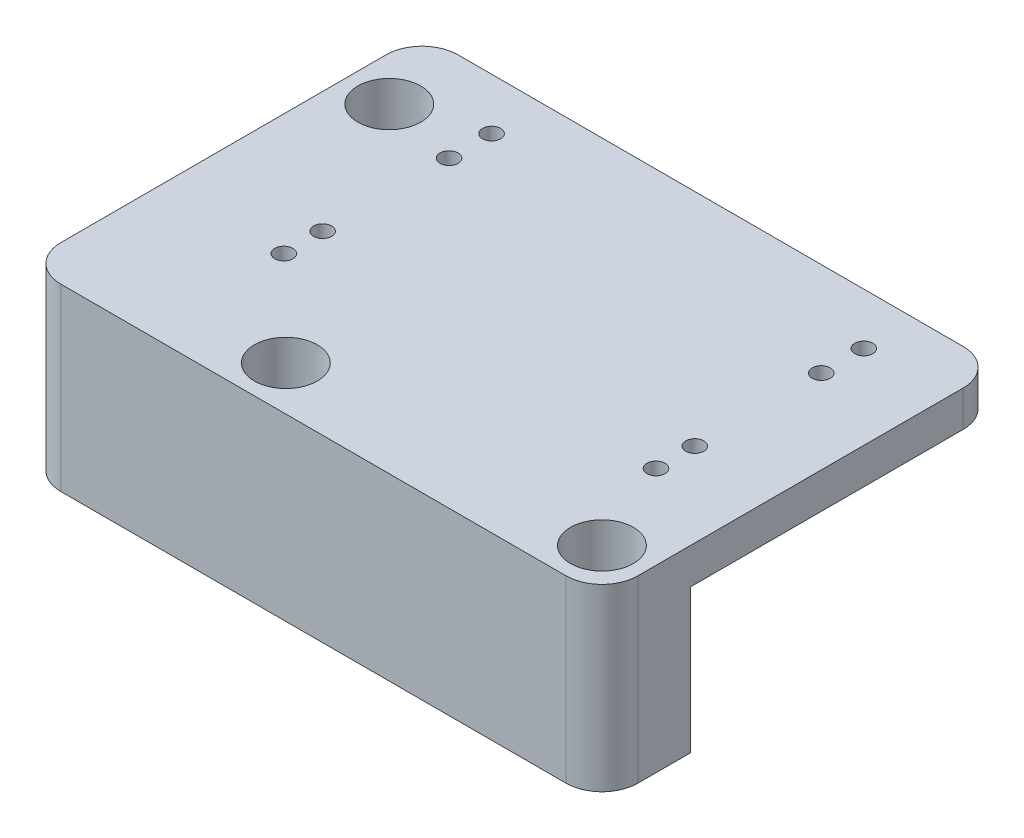
SolidWorks part; units mm, degrees
material "ABS"
ref_plane "Front Plane" through (0, 0, 0) normal (0, 0, 1) x (1, 0, 0)
ref_plane "Top Plane" through (0, 0, 0) normal (0, 1, 0) x (1, 0, 0)
ref_plane "Right Plane" through (0, 0, 0) normal (1, 0, 0) x (0, 0, -1)
sketch "Sketch1" plane through (0, 0, 0) normal (0, 1, 0) x (1, 0, 0)
  line L1 (-19.2405, -13.6398) -> (19.2405, -13.6398)
  line L2 (-19.2405, -13.6398) -> (-19.2405, 13.6398)
  line L3 (-19.2405, 13.6398) -> (19.2405, 13.6398)
  line L4 (19.2405, -13.6398) -> (19.2405, 13.6398)
  line L5 (-19.2405, -13.6398) -> (19.2405, 13.6398) construction
  line L6 (-19.2405, 13.6398) -> (19.2405, -13.6398) construction
  circle A0 centre (20.0279, -17.5514) radius 2.3241
  circle A1 centre (-7.9121, -17.5514) radius 2.3241
  circle A2 centre (-23.1521, 6.8326) radius 2.3241
  circle A3 centre (-23.1521, 6.8326) radius 3.9116
  circle A4 centre (-7.9121, -17.5514) radius 3.9116
  circle A5 centre (20.0279, -17.5514) radius 3.9116
  point P0 (0, 0)
  point P12 (-16.3703, -9.271)
  point P13 (-16.3703, -5.842)
  point P14 (-16.3703, 5.334)
  point P15 (-16.3703, 9.0932)
  point P16 (16.5227, -9.271)
  point P17 (16.5227, -5.842)
  point P18 (16.5227, 5.334)
  point P19 (16.5227, 9.0932)
  dimension "D1" = 4.6482
  dimension "D2" = 38.481
  dimension "D3" = 27.2796
  dimension "D4" = 15.24
  dimension "D5" = 43.18
  dimension "D6" = 24.384
  dimension "D7" = 2.8702
  dimension "D8" = 35.7632
  dimension "D9" = 4.3688
  dimension "D10" = 7.7978
  dimension "D11" = 18.9738
  dimension "D12" = 22.733
  dimension "D13" = 1.5875
  dimension "D14" = 1.5875
sketch "Sketch2" plane through (0, 0, 0) normal (0, 1, 0) x (1, 0, 0)
  line L1 (-27.0637, 13.6398) -> (23.9395, 13.6398)
  line L2 (-27.0637, 13.6398) -> (-27.0637, -21.463)
  line L3 (-27.0637, -21.463) -> (23.9395, -21.463)
  line L4 (23.9395, 13.6398) -> (23.9395, -21.463)
  line L5 (-27.0637, 13.6398) -> (23.9395, -21.463) construction
  line L6 (-27.0637, -21.463) -> (23.9395, 13.6398) construction
  line L7 (-19.2405, 13.6398) -> (19.2405, 13.6398) construction
  circle A0 centre (-7.9121, -17.5514) radius 3.9116 construction
  circle A1 centre (-23.1521, 6.8326) radius 3.9116 construction
  circle A2 centre (20.0279, -17.5514) radius 3.9116 construction
  point P4 (-1.5621, -3.9116)
extrude "Boss-Extrude1" add sketch "Sketch2" along normal blind 3.175
sketch "Sketch14" plane through (0, 0, 0) normal (0, -1, 0) x (1, 0, 0)
  line L0 (-27.0637, -13.6398) -> (-27.0637, 21.463)
  line L1 (-27.0637, 21.463) -> (23.9395, 21.463)
  line L2 (23.9395, 21.463) -> (23.9395, 13.6398)
  line L3 (23.9395, 21.463) -> (23.9395, -13.6398) construction
  line L4 (23.9395, 13.6398) -> (-19.2405, 13.6398)
  line L5 (-19.2405, 13.6398) -> (-19.2405, -13.6398)
  line L6 (-19.2405, -13.6398) -> (-27.0637, -13.6398)
  circle A0 centre (-7.9121, 17.5514) radius 3.9116 construction
extrude "Boss-Extrude3" add sketch "Sketch14" along normal blind 12.7
hole_wizard "M2x0.4 Tapped Hole2" positions "Sketch9" profile "Sketch8" tap size "M2x0.4" standard "ANSI Metric" end condition through all
sketch "Sketch9" plane through (0, 3.175, 0) normal (0, 1, 0) x (1, 0, 0)
  point P0 (-16.3703, 9.0932)
  point P3 (-16.3703, 5.334)
  point P6 (-16.3703, -5.842)
  point P9 (-16.3703, -9.271)
  point P12 (16.5227, -9.271)
  point P15 (16.5227, -5.842)
  point P18 (16.5227, 5.334)
  point P21 (16.5227, 9.0932)
sketch "Sketch8" plane through (-16.3703, 3.175, -9.0932) normal (1, 0, 0) x (0, 0, 1)
  line L0 (0, 0) -> (0, 15.875)
  line L1 (0, 15.875) -> (0.8, 15.875)
  line L2 (0.8, 15.875) -> (0.8, 0)
  line L5 (0.8, 0) -> (0, 0)
  line L11 (0, -6.35) -> (0, 107.95) construction
  dimension "Thread Major Dia." = 1.6
  dimension "Thru Tap Drill Depth" = 15.875
hole_wizard "CBORE for #4 Socket Head Cap Screw4" positions "Sketch18" profile "Sketch17" counterbore size "#4" standard "ANSI Inch" end condition through all
sketch "Sketch18" plane through (0, 3.175, 0) normal (0, 1, 0) x (1, 0, 0)
  point P0 (-23.1521, 6.8326)
  point P3 (-7.9121, -17.5514)
  point P6 (20.0279, -17.5514)
sketch "Sketch17" plane through (-23.1521, 3.175, -6.8326) normal (1, 0, 0) x (0, 0, 1)
  line L0 (0, 0) -> (0, 15.875)
  line L1 (0, 15.875) -> (1.6319, 15.875)
  line L3 (1.6319, 15.875) -> (1.6319, 12.4968)
  line L4 (1.6319, 12.4968) -> (2.7788, 12.4968)
  line L5 (2.7788, 12.4968) -> (2.7788, 0)
  line L7 (2.7788, 0) -> (0, 0)
  line L11 (0, -6.35) -> (0, 107.95) construction
  dimension "Thru Hole Dia." = 3.2639
  dimension "Thru Hole Depth" = 15.875
  dimension "C'Bore Dia." = 5.5575
  dimension "C'Bore Depth" = 12.4968
fillet "Fillet1" radius 3.175 4 edges at (23.9395, -4.7625, 21.463) (23.9395, 1.5875, -13.6398) (-27.0637, -4.7625, -13.6398) (-27.0637, -4.7625, 21.463)
